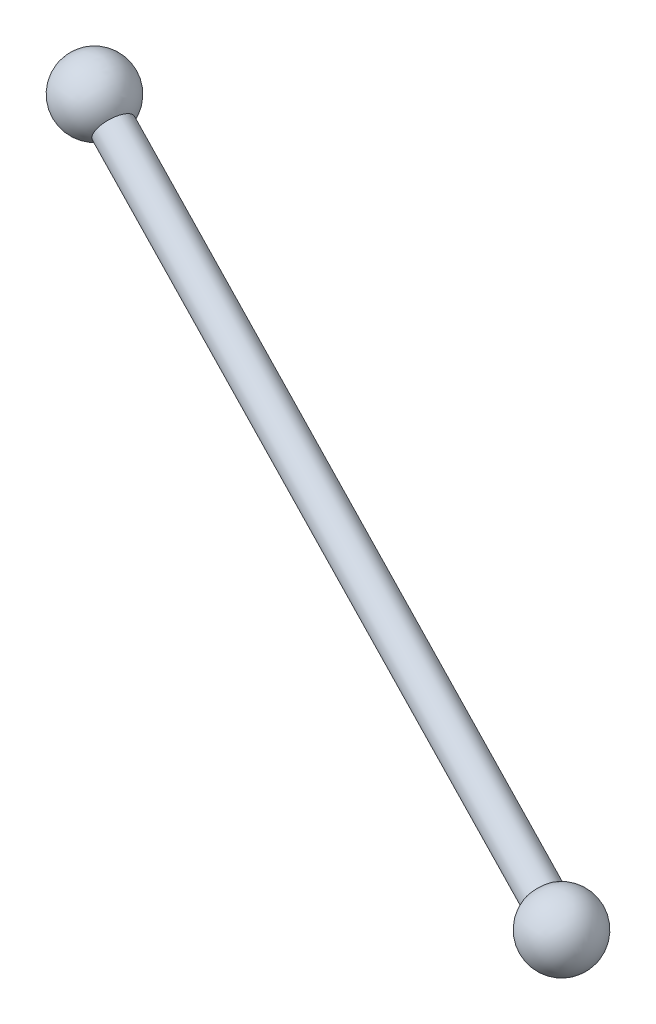
SolidWorks part; units mm, degrees
other "Compression Inner Strut"
other "Compression Inner Strut Left"
ref_plane "Front Plane" through (0, 0, 0) normal (0, 0, 1) x (1, 0, 0)
ref_plane "Top Plane" through (0, 0, 0) normal (0, 1, 0) x (1, 0, 0)
ref_plane "Right Plane" through (0, 0, 0) normal (1, 0, 0) x (0, 0, -1)
sketch3d "Three millimetre strut core sketch datum points"
  point P0 (-26.2917, -73, 0)
  point P1 (-21.3565, -80.6666, -4.1071)
  point P2 (-26.2917, -77.7222, 8.8148)
ref_plane "Three millimetre strut core sketch plane" through (-47.5081, -23.7622, -12.7298) normal (-0.8697, -0.435, -0.233) x (-0.2084, -0.1043, 0.9725)
sketch "Three millimetre strut core sketch" plane through (-47.5081, -23.7622, -12.7298) normal (-0.8697, -0.435, -0.233) x (-0.2084, -0.1043, 0.9725)
  circle A0 centre (13.0902, -53.5275) radius 1.5
extrude "Three millimetre strut core" add sketch "Three millimetre strut core sketch" along normal blind 64.3649 separate body
sketch3d "Ball end 1 axis line"
  line L0 (-26.2917, -73, -10) -> (-26.2917, -73, 10) construction
ref_axis "Ball end 1 axis" through (-26.2917, -73, -10) along (0, 0, 1)
sketch3d "Ball end 1 profile datum points"
  point P0 (-26.2917, -73, 0)
  point P1 (-16.2917, -73, 0)
  point P2 (-26.2917, -73, 10)
ref_plane "Ball end 1 profile plane" through (0, -73, 0) normal (0, -1, 0) x (-1, 0, 0)
sketch "Ball end 1 profile" plane through (0, -73, 0) normal (0, -1, 0) x (-1, 0, 0)
  line L0 (26.2917, -3) -> (26.2917, 3)
  arc A0 (26.2917, 3) -> (26.2917, -3) centre (26.2917, 0) ccw
revolve "Ball end 1" add sketch "Ball end 1 profile" angle 360 about axis through (-26.2917, -73, -10) along (0, 0, 1)
sketch3d "Ball end 2 axis line"
  line L0 (-82.2724, -101, -25) -> (-82.2724, -101, -5) construction
ref_axis "Ball end 2 axis" through (-82.2724, -101, -25) along (0, 0, 1)
sketch3d "Ball end 2 profile datum points"
  point P0 (-82.2724, -101, -15)
  point P1 (-72.2724, -101, -15)
  point P2 (-82.2724, -101, -5)
ref_plane "Ball end 2 profile plane" through (0, -101, 0) normal (0, -1, 0) x (-1, 0, 0)
sketch "Ball end 2 profile" plane through (0, -101, 0) normal (0, -1, 0) x (-1, 0, 0)
  line L0 (82.2724, 12) -> (82.2724, 18)
  arc A0 (82.2724, 18) -> (82.2724, 12) centre (82.2724, 15) ccw
revolve "Ball end 2" add sketch "Ball end 2 profile" angle 360 about axis through (-82.2724, -101, -25) along (0, 0, 1)
sketch3d "Mirror1 profile datum points"
  point P0 (0, 0, 0)
  point P1 (10, 0, 0)
  point P2 (0, 0, 10)
ref_plane "Mirror1 profile plane" through (0, 0, 0) normal (0, -1, 0) x (-1, 0, 0)
mirror "Mirror1" about plane through (0, 0, 0) normal (0, -1, 0) of bodies 103
delete or keep bodies "Remove1" type delete bodies bodies 103
